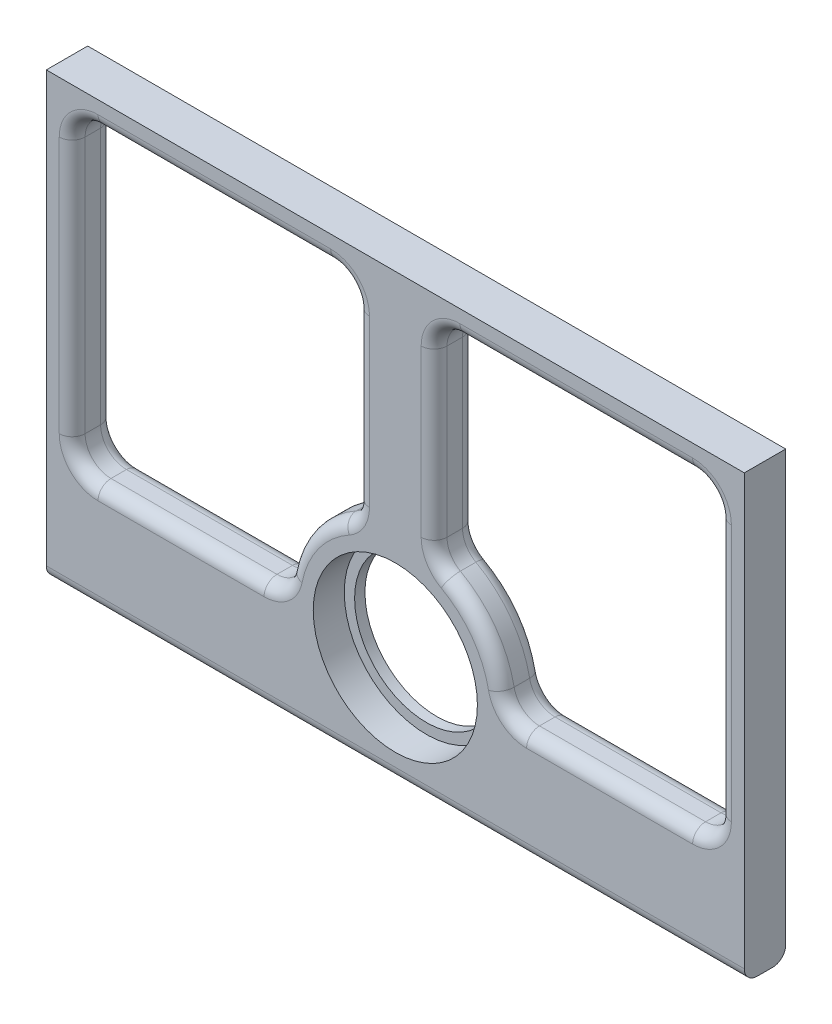
SolidWorks part; units mm, degrees
material "AISI 4340 Steel, annealed"
ref_plane "Front Plane" through (0, 0, 0) normal (0, 0, 1) x (1, 0, 0)
ref_plane "Top Plane" through (0, 0, 0) normal (0, 1, 0) x (1, 0, 0)
ref_plane "Right Plane" through (0, 0, 0) normal (1, 0, 0) x (0, 0, -1)
sketch "Sketch1" plane through (0, 0, 0) normal (0, 0, 1) x (1, 0, 0)
  circle A0 centre (0, 0) radius 31.75
  circle A1 centre (0, 0) radius 41.75
  dimension "D1" = 63.5
  dimension "D2" = 10
extrude "Bearing holder" add sketch "Sketch1" along normal blind 16
sketch "Sketch2" plane through (0, 0, 0) normal (0, 0, -1) x (-1, 0, 0)
  circle A0 centre (0, 0) radius 31.75 construction
  circle A1 centre (0, 0) radius 31.75
  circle A2 centre (0, 0) radius 27.75
  dimension "D1" = 4
extrude "Bearing lip" add sketch "Sketch2" against normal blind 4
sketch "Sketch3" plane through (0, 0, 16) normal (0, 0, 1) x (1, 0, 0)
  line L0 (-135, -41.75) -> (-125, -41.75)
  line L1 (-125, 0) -> (-125, 119.38)
  line L2 (-125, 119.38) -> (-15, 119.38)
  line L3 (125, 119.38) -> (125, 0)
  line L4 (125, -41.75) -> (135, -41.75)
  line L5 (135, -41.75) -> (135, 129.38)
  line L6 (135, 129.38) -> (-135, 129.38)
  line L7 (-135, 129.38) -> (-135, -41.75)
  line L8 (-41.75, -41.75) -> (-125, -41.75)
  line L9 (41.75, -41.75) -> (125, -41.75)
  line L10 (41.75, 0) -> (125, 0)
  line L11 (-41.75, 0) -> (-125, 0)
  line L12 (-15, 119.38) -> (-15, 38.9623)
  line L13 (15, 119.38) -> (15, 38.9623)
  line L14 (15, 119.38) -> (125, 119.38)
  line L17 (-41.75, 0) -> (-36.75, 0)
  line L18 (36.75, 0) -> (41.75, 0)
  line L19 (41.75, -41.75) -> (-41.75, -41.75)
  circle A0 centre (0, 0) radius 41.75 construction
  arc A2 (15, 38.9623) -> (-15, 38.9623) centre (0, 0) ccw
  circle A5 centre (0, 0) radius 36.75
  arc A6 (-36.75, 0) -> (36.75, 0) centre (0, 0) ccw
  dimension "D1" = 10
  dimension "D2" = 10
  dimension "D3" = 10
  dimension "D4" = 270
  dimension "D5" = 129.38
  dimension "D6" = 15
  dimension "D7" = 30
  dimension "D8" = 135
  dimension "D9" = 5
extrude "Box adapter" add sketch "Sketch3" against normal blind 16
fillet "Structural fillets" radius 10 10 edges at (41.75, 0, 8) (15, 38.9623, 8) (-41.75, 0, 8) (-15, 38.9623, 8) (-125, 0, 8) (125, 0, 8) (-15, 119.38, 8) (125, 119.38, 8) (15, 119.38, 8) (-125, 119.38, 8)
fillet "Smaller fillets" radius 5 42 edges at (-17.9289, 116.4511, 0) (-15, 77.3454, 0) (-15, 77.3454, 16) (-16.3887, 40.2269, 0) (-33.7219, 24.6149, 0) (-44.4234, 2.2759, 0) (-82.8873, 0, 16) (-82.8873, 0, 0) (-122.0711, 2.9289, 0) (-125, 59.69, 16) (-125, 59.69, 0) (-122.0711, 116.4511, 0) (122.0711, 116.4511, 0) (125, 59.69, 0) (125, 59.69, 16) (122.0711, 2.9289, 0) (82.8873, 0, 0) (82.8873, 0, 16) (44.4234, 2.2759, 0) (33.7219, 24.6149, 0) (16.3887, 40.2269, 0) (15, 77.3454, 16) (15, 77.3454, 0) (17.9289, 116.4511, 0) (122.0711, 116.4511, 16) (122.0711, 2.9289, 16) (44.4234, 2.2759, 16) (33.7219, 24.6149, 16) (16.3887, 40.2269, 16) (17.9289, 116.4511, 16) (-17.9289, 116.4511, 16) (-16.3887, 40.2269, 16) (-33.7219, 24.6149, 16) (-44.4234, 2.2759, 16) (-122.0711, 2.9289, 16) (-122.0711, 116.4511, 16) (0, -41.75, 0) (0, -41.75, 16) (-70, 119.38, 0) (-70, 119.38, 16) (70, 119.38, 0) (70, 119.38, 16)
